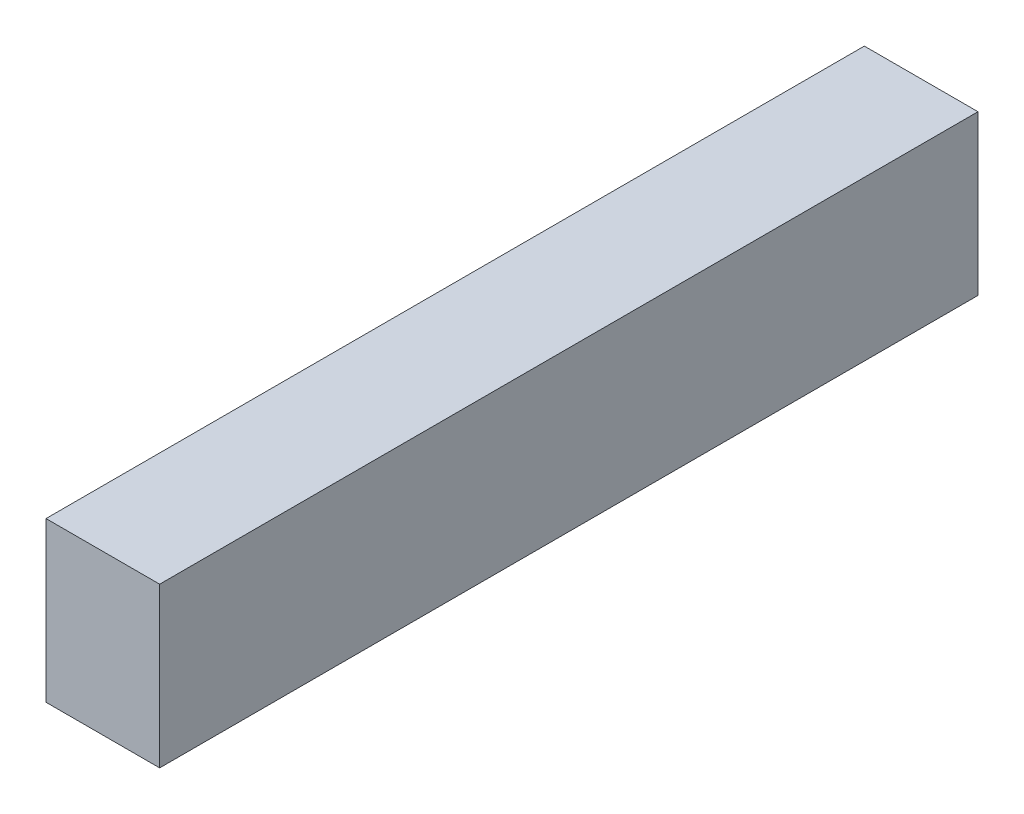
SolidWorks part; units mm, degrees
material "Silicon Rubber"
ref_plane "Front Plane" through (0, 0, 0) normal (0, 0, 1) x (1, 0, 0)
ref_plane "Top Plane" through (0, 0, 0) normal (0, 1, 0) x (1, 0, 0)
ref_plane "Right Plane" through (0, 0, 0) normal (1, 0, 0) x (0, 0, -1)
sketch "Sketch1" plane through (0, 0, 0) normal (1, 0, 0) x (0, 0, -1)
  line L1 (-90, -17.5) -> (90, -17.5)
  line L2 (-90, -17.5) -> (-90, 17.5)
  line L3 (-90, 17.5) -> (90, 17.5)
  line L4 (90, -17.5) -> (90, 17.5)
  line L5 (-90, -17.5) -> (90, 17.5) construction
  line L6 (-90, 17.5) -> (90, -17.5) construction
  point P0 (0, 0)
  dimension "D1" = 180
  dimension "D2" = 35
extrude "Boss-Extrude1" add sketch "Sketch1" along normal blind 25
